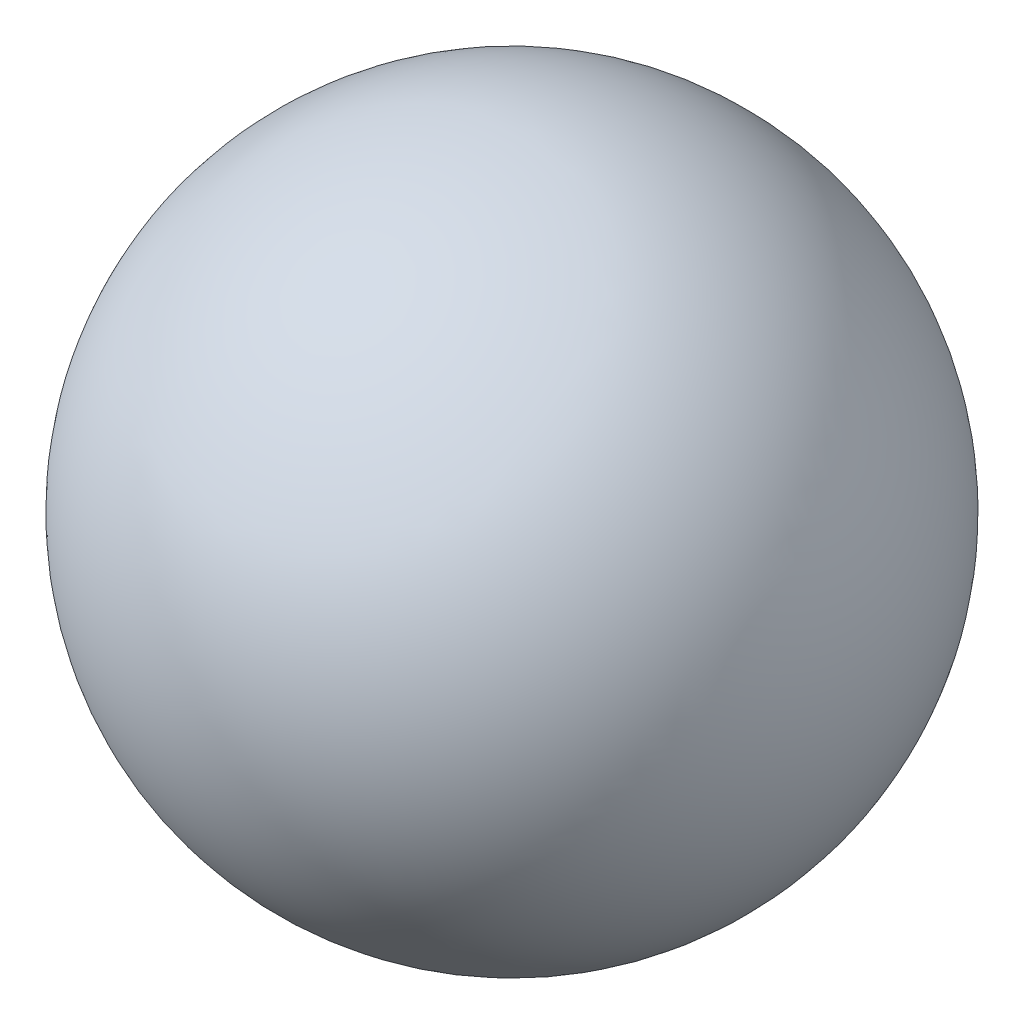
SolidWorks part; units mm, degrees
ref_plane "Front Plane" through (0, 0, 0) normal (0, 0, 1) x (1, 0, 0)
ref_plane "Top Plane" through (0, 0, 0) normal (0, 1, 0) x (1, 0, 0)
ref_plane "Right Plane" through (0, 0, 0) normal (1, 0, 0) x (0, 0, -1)
sketch "Sketch1" plane through (0, 0, 0) normal (0, 0, 1) x (1, 0, 0)
  line L0 (-12, 0) -> (12, 0)
  arc A0 (12, 0) -> (-12, 0) centre (0, 0) cw
  dimension "D1" = 24
revolve "Revolve1" add sketch "Sketch1" angle 360 about L0
scale "Scale1" scale about centroid uniform scaling yes scale factor 1.413611
